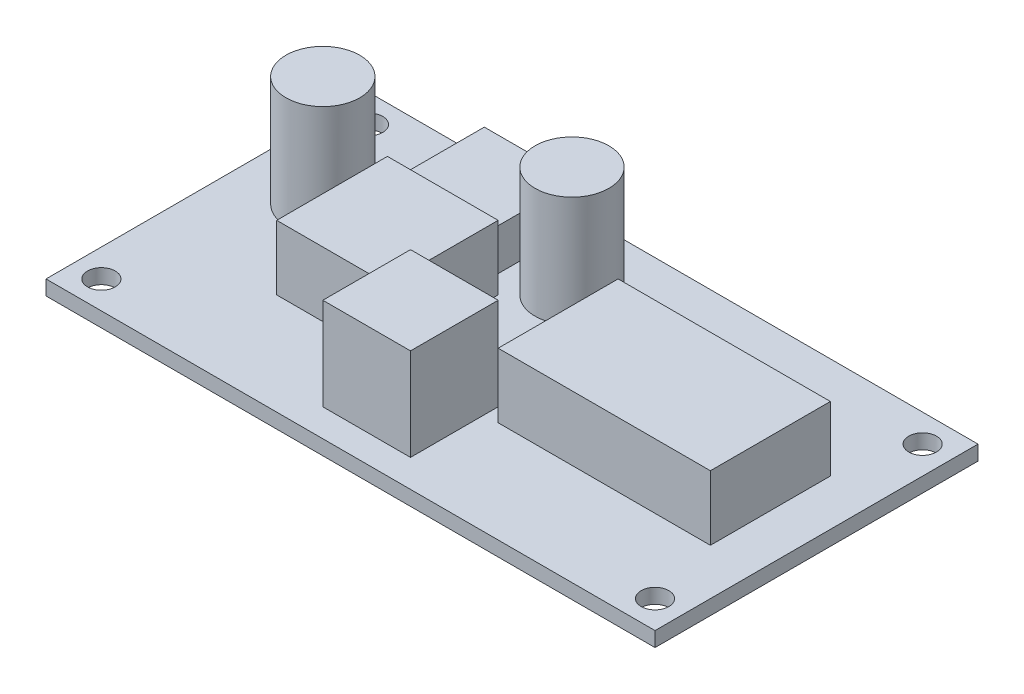
SolidWorks part; units mm, degrees
ref_plane "Front Plane" through (0, 0, 0) normal (0, 0, 1) x (1, 0, 0)
ref_plane "Top Plane" through (0, 0, 0) normal (0, 1, 0) x (1, 0, 0)
ref_plane "Right Plane" through (0, 0, 0) normal (1, 0, 0) x (0, 0, -1)
other "Configuration Table"
sketch "Sketch1" plane through (0, 0, 0) normal (0, 1, 0) x (1, 0, 0)
  line L1 (0, 0) -> (66, 0)
  line L2 (0, 0) -> (0, 35)
  line L3 (0, 35) -> (66, 35)
  line L4 (66, 0) -> (66, 35)
extrude "PCB" add sketch "Sketch1" along normal blind 1.6
sketch "Sketch2" plane through (0, 0, 0) normal (0, 1, 0) x (1, 0, 0)
  circle A0 centre (3, 3) radius 1.5
extrude "Mount_hole_1" cut sketch "Sketch2" against normal through all and the other way through all
sketch "Sketch3" plane through (0, 0, 0) normal (0, 1, 0) x (1, 0, 0)
  circle A0 centre (63, 3) radius 1.5
extrude "Mount_hole_2" cut sketch "Sketch3" against normal through all and the other way through all
sketch "Sketch4" plane through (0, 0, 0) normal (0, 1, 0) x (1, 0, 0)
  circle A0 centre (3, 32) radius 1.5
extrude "Mount_hole_3" cut sketch "Sketch4" against normal through all and the other way through all
sketch "Sketch5" plane through (0, 0, 0) normal (0, 1, 0) x (1, 0, 0)
  circle A0 centre (63, 32) radius 1.5
extrude "Mount_hole_4" cut sketch "Sketch5" against normal through all and the other way through all
sketch "Sketch6" plane through (0, 0, 0) normal (0, 1, 0) x (1, 0, 0)
  line L1 (38, 11) -> (61, 11)
  line L2 (38, 11) -> (38, 24)
  line L3 (38, 24) -> (61, 24)
  line L4 (61, 11) -> (61, 24)
extrude "Voltmeter_display" add sketch "Sketch6" along normal blind 7 from offset 1.6
sketch "Sketch7" plane through (0, 0, 0) normal (0, 1, 0) x (1, 0, 0)
  line L1 (14, 11) -> (26, 11)
  line L2 (14, 11) -> (14, 23)
  line L3 (14, 23) -> (26, 23)
  line L4 (26, 11) -> (26, 23)
extrude "Inductor" add sketch "Sketch7" along normal blind 7 from offset 1.6
sketch "Sketch8" plane through (0, 0, 0) normal (0, 1, 0) x (1, 0, 0)
  circle A0 centre (8, 22) radius 4
extrude "Cap_in" add sketch "Sketch8" along normal blind 12 from offset 1.6
sketch "Sketch9" plane through (0, 0, 0) normal (0, 1, 0) x (1, 0, 0)
  circle A0 centre (30, 27) radius 4
extrude "Cap_out" add sketch "Sketch9" along normal blind 12 from offset 1.6
sketch "Sketch10" plane through (0, 0, 0) normal (0, 1, 0) x (1, 0, 0)
  line L1 (27, 3) -> (36.5, 3)
  line L2 (27, 3) -> (27, 12.5)
  line L3 (27, 12.5) -> (36.5, 12.5)
  line L4 (36.5, 3) -> (36.5, 12.5)
extrude "Trim_pot" add sketch "Sketch10" along normal blind 10 from offset 1.6
sketch "Sketch11" plane through (0, 0, 0) normal (0, 1, 0) x (1, 0, 0)
  line L1 (14, 25) -> (24, 25)
  line L2 (14, 25) -> (14, 33.5)
  line L3 (14, 33.5) -> (24, 33.5)
  line L4 (24, 25) -> (24, 33.5)
extrude "LM2596" add sketch "Sketch11" along normal blind 4.5 from offset 1.6
